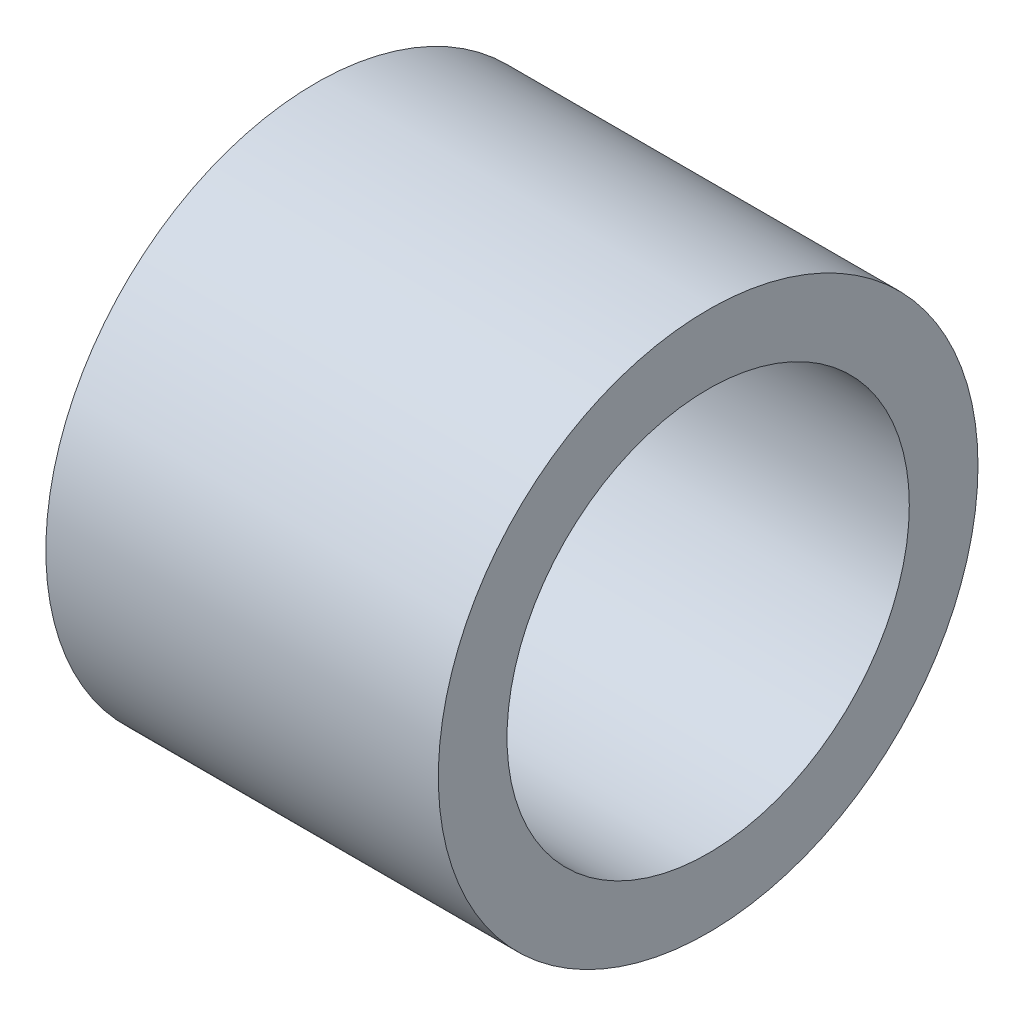
SolidWorks part; units mm, degrees
ref_plane "Front Plane" through (0, 0, 0) normal (0, 0, 1) x (1, 0, 0)
ref_plane "Top Plane" through (0, 0, 0) normal (0, 1, 0) x (1, 0, 0)
ref_plane "Right Plane" through (0, 0, 0) normal (1, 0, 0) x (0, 0, -1)
sketch "Sketch1" plane through (0, 0, 0) normal (1, 0, 0) x (0, 0, -1)
  circle A0 centre (0, 0) radius 5.5
  circle A1 centre (0, 0) radius 4.1
  dimension "D1" = 11
  dimension "D2" = 8.2
extrude "Boss-Extrude1" add sketch "Sketch1" along normal blind 8
